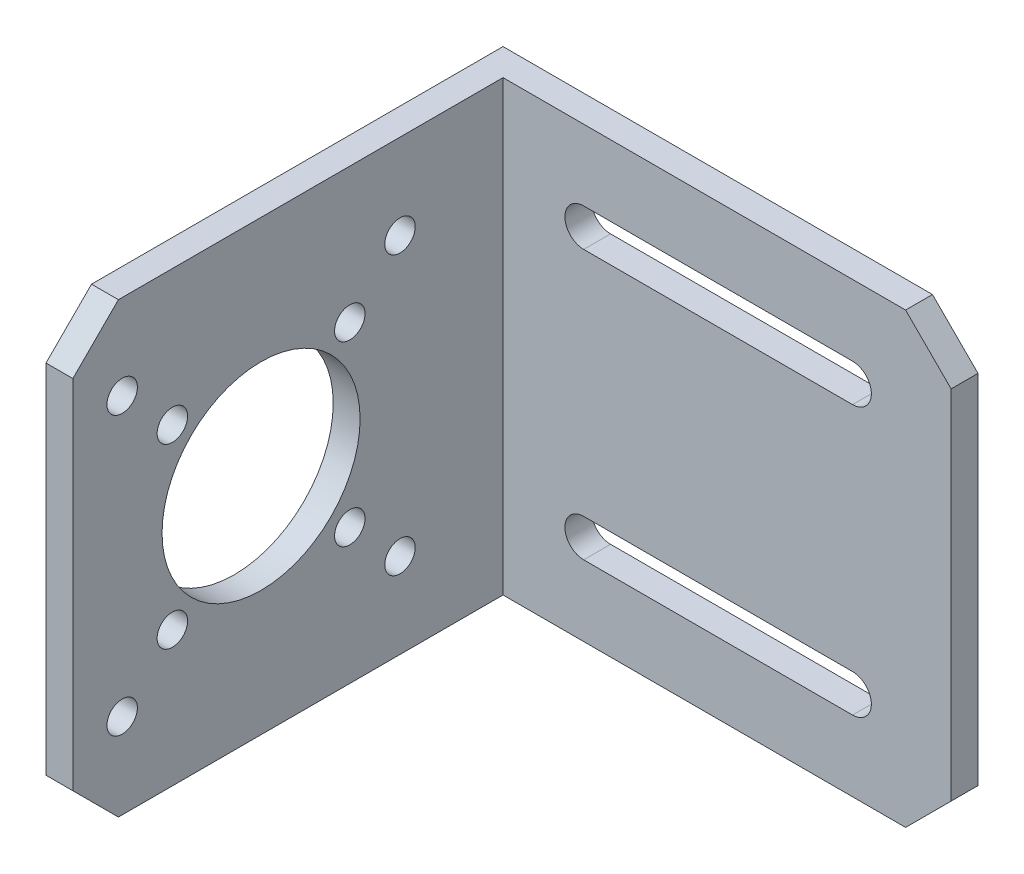
SolidWorks part; units mm, degrees
ref_plane "Front Plane" through (0, 0, 0) normal (0, 0, 1) x (1, 0, 0)
ref_plane "Top Plane" through (0, 0, 0) normal (0, 1, 0) x (1, 0, 0)
ref_plane "Right Plane" through (0, 0, 0) normal (1, 0, 0) x (0, 0, -1)
sketch "Sketch1" plane through (0, 0, 0) normal (0, 0, 1) x (1, 0, 0)
  line L1 (0, 0) -> (53, 0)
  line L2 (0, 0) -> (0, 50)
  line L3 (0, 50) -> (53, 50)
  line L4 (53, 0) -> (53, 50)
  dimension "D1" = 50
  dimension "D2" = 53
extrude "Boss-Extrude1" add sketch "Sketch1" along normal blind 3
sketch "Sketch2" plane through (0, 0, 3) normal (0, 0, 1) x (1, 0, 0)
  line L0 (42, 50) -> (42, 0) construction
  line L1 (53, 50) -> (0, 50) construction
  line L2 (0, 0) -> (53, 0) construction
  line L3 (53, 0) -> (53, 50) construction
  line L4 (53, 25) -> (0, 25) construction
  line L5 (0, 50) -> (0, 0) construction
  line L6 (0, 40) -> (53, 40) construction
  line L7 (42, 40) -> (12, 40) construction
  line L8 (42, 37.9) -> (12, 37.9)
  line L9 (42, 42.1) -> (12, 42.1)
  line L10 (42, 10) -> (12, 10) construction
  line L11 (42, 12.1) -> (12, 12.1)
  line L12 (42, 7.9) -> (12, 7.9)
  arc A0 (42, 37.9) -> (42, 42.1) centre (42, 40) ccw
  arc A1 (12, 42.1) -> (12, 37.9) centre (12, 40) ccw
  arc A2 (42, 12.1) -> (42, 7.9) centre (42, 10) cw
  arc A3 (12, 7.9) -> (12, 12.1) centre (12, 10) cw
  point P16 (27, 40)
  point P23 (27, 10)
  dimension "D4" = 2.1
  dimension "D1" = 11
  dimension "D2" = 15
  dimension "D3" = 30
extrude "Cut-Extrude1" cut sketch "Sketch2" against normal through all
sketch "Sketch3" plane through (0, 0, 3) normal (0, 0, 1) x (1, 0, 0)
  line L0 (0, 0) -> (53, 0) construction
  line L1 (0, 50) -> (3, 50)
  line L2 (0, 50) -> (0, 0)
  line L3 (0, 0) -> (3, 0)
  line L4 (3, 50) -> (3, 0)
  dimension "D1" = 3
extrude "Boss-Extrude2" add sketch "Sketch3" along normal blind 48
sketch "Sketch4" plane through (0, 0, 0) normal (-1, 0, 0) x (0, 0, 1)
  line L0 (51, 25) -> (0, 25) construction
  line L1 (51, 50) -> (51, 0) construction
  line L2 (0, 50) -> (0, 0) construction
  circle A0 centre (30, 25) radius 11.05
  dimension "D1" = 21
  dimension "D2" = 22.1
extrude "Cut-Extrude2" cut sketch "Sketch4" against normal through all
hole_wizard "M3 Clearance Hole1" positions "Sketch5" profile "Sketch7" hole size "M3" standard "ANSI Metric" end condition through all
sketch "Sketch5" plane through (0, 0, 0) normal (-1, 0, 0) x (0, 0, 1)
  line L1 (14.5, 40.5) -> (45.5, 40.5) construction
  line L2 (14.5, 40.5) -> (14.5, 9.5) construction
  line L3 (14.5, 9.5) -> (45.5, 9.5) construction
  line L4 (45.5, 40.5) -> (45.5, 9.5) construction
  line L5 (14.5, 40.5) -> (45.5, 9.5) construction
  line L6 (14.5, 9.5) -> (45.5, 40.5) construction
  point P1 (45.5, 9.5)
  point P54 (14.5, 40.5)
  point P55 (14.5, 9.5)
  point P56 (45.5, 40.5)
  dimension "D1" = 31
  dimension "D2" = 31
sketch "Sketch7" plane through (0, 9.5, 45.5) normal (0, 1, 0) x (0, 0, 1)
  line L0 (0, 0) -> (0, 53)
  line L1 (0, 53) -> (1.7, 53)
  line L2 (1.7, 53) -> (1.7, 0)
  line L5 (1.7, 0) -> (0, 0)
  line L11 (0, -6.35) -> (0, 107.95) construction
  dimension "Thru Hole Dia." = 3.4
  dimension "Thru Hole Depth" = 53
hole_wizard "M3 Clearance Hole2" positions "Sketch8" profile "Sketch9" hole size "M3" standard "ANSI Metric" end condition through all
sketch "Sketch8" plane through (0, 0, 0) normal (-1, 0, 0) x (0, 0, 1)
  line L1 (20.1005, 34.8995) -> (39.8995, 34.8995)
  line L2 (20.1005, 34.8995) -> (20.1005, 15.1005)
  line L3 (20.1005, 15.1005) -> (39.8995, 15.1005)
  line L4 (39.8995, 34.8995) -> (39.8995, 15.1005)
  line L5 (20.1005, 34.8995) -> (39.8995, 15.1005) construction
  line L6 (20.1005, 15.1005) -> (39.8995, 34.8995) construction
  circle A0 centre (30, 25) radius 14 construction
  point P6 (39.8995, 15.1005)
  point P73 (20.1005, 34.8995)
  point P74 (20.1005, 15.1005)
  point P75 (39.8995, 34.8995)
  dimension "D1" = 28
sketch "Sketch9" plane through (0, 34.8995, 39.8995) normal (0, 1, 0) x (0, 0, 1)
  line L0 (0, 0) -> (0, 53)
  line L1 (0, 53) -> (1.7, 53)
  line L2 (1.7, 53) -> (1.7, 0)
  line L5 (1.7, 0) -> (0, 0)
  line L11 (0, -6.35) -> (0, 107.95) construction
  dimension "Thru Hole Dia." = 3.4
  dimension "Thru Hole Depth" = 53
chamfer "Chamfer1" distance 5.08 angle 45 4 edges at (53, 0, 1.5) (53, 50, 1.5) (1.5, 50, 51) (1.5, 0, 51)
